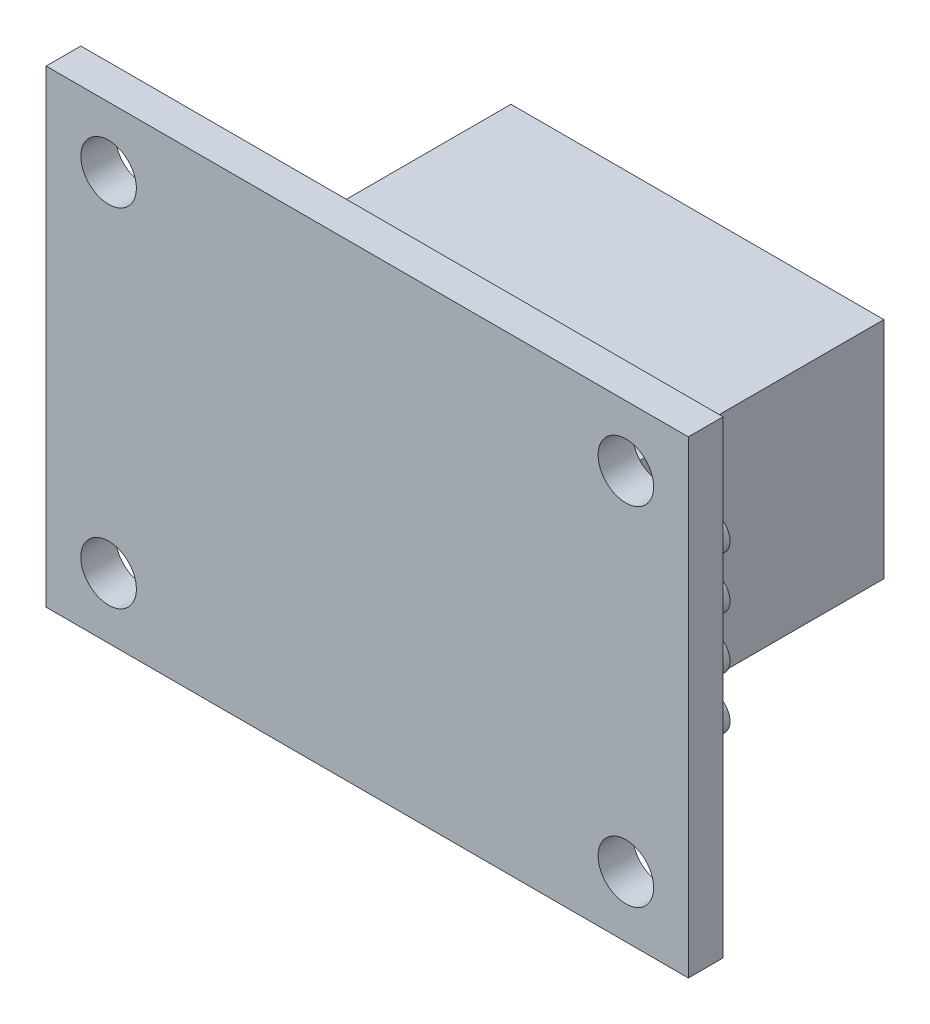
SolidWorks part; units mm, degrees
ref_plane "前基準面" through (0, 0, 0) normal (0, 0, 1) x (1, 0, 0)
ref_plane "上基準面" through (0, 0, 0) normal (0, 1, 0) x (1, 0, 0)
ref_plane "右基準面" through (0, 0, 0) normal (1, 0, 0) x (0, 0, -1)
sketch "草圖1" plane through (0, 0, 0) normal (0, 0, 1) x (1, 0, 0)
  line L1 (-21.1263, 9.6555) -> (15.8737, 9.6555)
  line L2 (-21.1263, 9.6555) -> (-21.1263, -17.3445)
  line L3 (-21.1263, -17.3445) -> (15.8737, -17.3445)
  line L4 (15.8737, 9.6555) -> (15.8737, -17.3445)
  dimension "D1" = 37
  dimension "D2" = 27
extrude "填料-伸長1" add sketch "草圖1" along normal blind 2
sketch "草圖2" plane through (0, 0, 0) normal (0, 0, -1) x (-1, 0, 0)
  line L0 (21.1263, -17.3445) -> (-15.8737, -17.3445) construction
  line L1 (21.1263, 9.6555) -> (21.1263, -17.3445) construction
  circle A0 centre (-12.2737, 6.1555) radius 1.6
  circle A1 centre (-12.2737, -13.8445) radius 1.6
  circle A2 centre (17.5263, -13.8445) radius 1.6
  circle A3 centre (17.5263, 6.1555) radius 1.6
  dimension "D1" = 3.2
  dimension "D2" = 3.2
  dimension "D3" = 3.2
  dimension "D4" = 3.2
  dimension "D5" = 29.8
  dimension "D6" = 20
  dimension "D7" = 29.8
  dimension "D9" = 3.6
  dimension "D10" = 3.6
  dimension "D8" = 3.5
extrude "除料-伸長1" cut sketch "草圖2" against normal through all
sketch "草圖3" plane through (0, 0, 0) normal (0, 0, -1) x (-1, 0, 0)
  line L1 (-8.1373, 2.1377) -> (13.3478, 2.1377)
  line L2 (-8.1373, 2.1377) -> (-8.1373, -10.7955)
  line L3 (-8.1373, -10.7955) -> (13.3478, -10.7955)
  line L4 (13.3478, 2.1377) -> (13.3478, -10.7955)
extrude "填料-伸長2" add sketch "草圖3" along normal blind 17
sketch "草圖4" plane through (0, 0, 0) normal (0, 0, -1) x (-1, 0, 0)
  circle A0 centre (-12.2737, -2.3445) radius 1
  circle A1 centre (-12.2737, -5.3445) radius 1
  circle A2 centre (-12.2737, -8.3445) radius 1
  circle A5 centre (-12.2737, 0.6555) radius 1
  circle A6 centre (-12.2737, 6.1555) radius 1.6 construction
  dimension "D1" = 2
  dimension "D2" = 2
  dimension "D3" = 2
  dimension "D4" = 3
  dimension "D5" = 3
  dimension "D6" = 2
  dimension "D7" = 3
  dimension "D8" = 5.5
extrude "填料-伸長3" add sketch "草圖4" along normal blind 3
